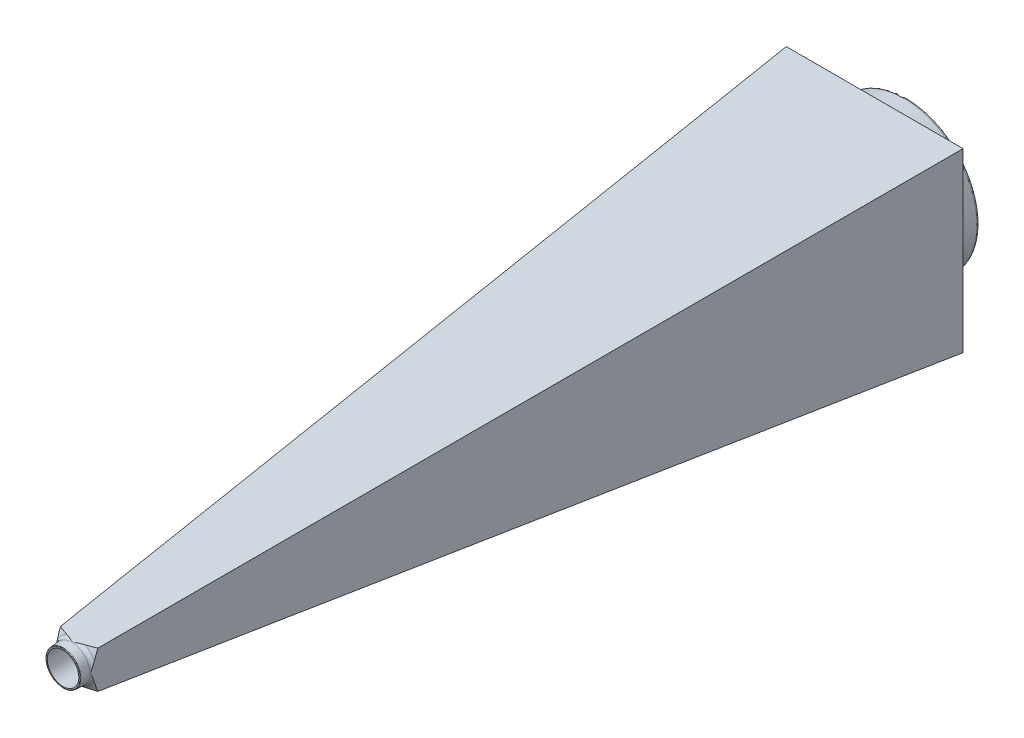
SolidWorks part; units mm, degrees
ref_plane "front" through (0, 0, 0) normal (0, 0, 1) x (1, 0, 0)
ref_plane "top" through (0, 0, 0) normal (0, 1, 0) x (1, 0, 0)
ref_plane "right" through (0, 0, 0) normal (1, 0, 0) x (0, 0, -1)
ref_axis "Axis1" through (0, 0, 50) along (0, 0, -1)
sketch "Sketch1" plane through (0, 0, 0) normal (1, 0, 0) x (0, 0, -1)
  line L0 (17.1291, 1.4986) -> (104.775, 9.1666)
  line L1 (17.1291, 3.0203) -> (104.775, 18.4747)
  line L2 (17.1291, 0) -> (104.775, 0) construction
  line L3 (104.775, 0) -> (104.775, 9.1666)
  line L4 (17.1291, 0) -> (17.1291, 1.4986)
  line L5 (17.1291, 2.3312) -> (34.9942, 4.7625)
  line L6 (72.2499, 9.1273) -> (89.0031, 11.2437)
  line L8 (104.775, 5.9795) -> (101.6, 5.7017)
  line L14 (103.9796, 4.0173) -> (43.9655, 1.397)
  line L15 (17.1291, 1.397) -> (43.9655, 1.397)
  point P0 (101.6, 8.8888)
  dimension "D2" = 10
  dimension "D3" = 17.7777
  dimension "D4" = 2.9972
  dimension "D5" = 3.175
  dimension "D6" = 6.0406
  dimension "D7" = 2.25
  dimension "D8" = 87.6459
  dimension "D9" = 17.1291
  dimension "D10" = 101.6
  dimension "D11" = 5
  dimension "D12" = 7.2
  dimension "D15" = 3.175
  dimension "D19" = 2.794
  dimension "D20" = 2.5
ref_plane "Plane1" through (0, 0, -17.1291) normal (0, 0, -1) x (-1, 0, 0)
ref_plane "Plane2" through (0, 0, -104.775) normal (0, 0, -1) x (-1, 0, 0)
sketch "Sketch2" plane through (0, 0, -17.1291) normal (0, 0, -1) x (-1, 0, 0)
  line L1 (1.4986, 1.4986) -> (-1.4986, 1.4986)
  line L2 (1.4986, 1.4986) -> (1.4986, -1.4986)
  line L3 (1.4986, -1.4986) -> (-1.4986, -1.4986)
  line L4 (-1.4986, 1.4986) -> (-1.4986, -1.4986)
  point P4 (-1.4986, 0)
sketch "Sketch3" plane through (0, 0, -104.775) normal (0, 0, -1) x (-1, 0, 0)
  line L1 (9.1666, 9.1666) -> (-9.1666, 9.1666)
  line L2 (9.1666, 9.1666) -> (9.1666, -9.1666)
  line L3 (9.1666, -9.1666) -> (-9.1666, -9.1666)
  line L4 (-9.1666, 9.1666) -> (-9.1666, -9.1666)
  point P4 (-9.1666, 0)
sketch3d "3DSketch1"
  line L0 (9.1666, 9.1666, -104.775) -> (1.4986, 1.4986, -17.1291)
sketch "Sketch17" plane through (0, 0, 0) normal (1, 0, 0) x (0, 0, -1)
  line L0 (105.41, 15.875) -> (105.41, 0)
  line L1 (105.41, 0) -> (17.1291, 0)
  line L2 (17.1291, 0) -> (17.1291, 2.1639)
  line L3 (72.2499, 9.1273) -> (89.0031, 11.2437) construction
  line L4 (105.41, 0) -> (124.5541, 0) construction
  line L6 (69.1652, 8.7376) -> (40.5902, 8.7376)
  line L7 (105.41, 15.875) -> (69.1652, 15.875)
  line L8 (69.1652, 15.875) -> (69.1652, 8.7376)
  line L9 (40.5902, 8.7376) -> (40.5902, 5.1277)
  line L10 (40.5902, 5.1277) -> (17.1291, 2.1639)
  dimension "D1" = 3.81
  dimension "D2" = 28.575
  dimension "D3" = 17.4752
  dimension "D4" = 31.75
revolve "BR-00 Lathe Initial" add sketch "Sketch17" angle 360 about L4
sketch "Sketch11" plane through (0, 0, 0) normal (1, 0, 0) x (0, 0, -1)
  line L5 (16.1202, 1.5875) -> (52.6835, 1.5875)
  line L6 (52.6835, 1.5875) -> (52.6835, 0)
  line L7 (17.1291, 0) -> (104.775, 0) construction
  line L8 (52.6835, 0) -> (16.1202, 0)
  line L9 (16.1202, 0) -> (16.1202, 1.5875)
  line L10 (16.1202, 0) -> (14.1068, 0) construction
  dimension "D2" = 3.175
revolve "CR-00 Bore at tip" cut sketch "Sketch11" angle 360 about axis through (0, 0, 50) along (0, 0, -1)
sketch "Sketch22" plane through (0, 0, 0) normal (0, 1, 0) x (1, 0, 0)
  line L0 (2.159, 14.5891) -> (5.1308, 14.5891)
  line L1 (5.1308, 14.5891) -> (5.1308, 38.1133)
  line L2 (5.1308, 38.1133) -> (2.159, 14.5891)
  line L3 (0, 0) -> (0, 16.6658)
  line L4 (-2.1639, 17.1291) -> (2.1639, 17.1291) construction
  line L5 (5.1308, 27.9803) -> (3.4391, 14.5891)
  line L6 (5.1308, 17.8473) -> (4.7192, 14.5891)
  line L7 (0, 17.1291) -> (7.3692, 17.1291)
  line L8 (6.3908, 37.9541) -> (3.419, 14.4299) construction
  line L9 (7.6508, 37.7949) -> (4.679, 14.2707) construction
  line L10 (-1.5875, 17.1291) -> (1.5875, 17.1291) construction
  dimension "D1" = 7.2
  dimension "D2" = 2.54
  dimension "D3" = 2.159
  dimension "D4" = 5.1308
  dimension "D5" = 1.27
  dimension "D6" = 1.27
sketch "Sketch16" plane through (0, 0, 0) normal (1, 0, 0) x (0, 0, -1)
  line L0 (15.5968, 0.762) -> (17.6371, 0.762)
  line L1 (17.6371, 0.762) -> (17.6371, 1.5367) construction
  line L2 (17.6371, 1.5367) -> (18.3305, 1.5974) construction
  line L3 (21.2443, 2.0697) -> (26.4988, 11.1707)
  line L4 (26.4988, 11.1707) -> (15.5968, 11.1707)
  line L5 (15.5968, 11.1707) -> (15.5968, 0.762)
  line L6 (17.1291, 0) -> (17.1291, 1.4986) construction
  line L7 (16.4674, 0) -> (13.7912, 0) construction
  line L8 (18.3305, 1.5974) -> (18.3305, 1.9038) construction
  line L9 (18.3305, 1.9038) -> (18.6531, 1.9038) construction
  line L10 (18.6531, 1.9038) -> (18.6531, 1.6256) construction
  line L11 (18.6531, 1.6256) -> (18.2177, 1.5875) construction
  line L12 (19.9597, 1.7399) -> (19.9597, 1.5875)
  line L13 (19.9597, 1.5875) -> (18.2177, 1.5875) construction
  line L14 (19.9597, 1.7399) -> (20.8487, 1.8177)
  line L15 (19.9597, 1.5875) -> (20.472, 1.5875)
  line L16 (20.472, 1.5875) -> (20.472, 0.762)
  line L17 (20.472, 0.762) -> (17.6371, 0.762)
  arc A0 (20.8487, 1.8177) -> (21.2443, 2.0697) centre (20.8044, 2.3237) ccw
  dimension "D5" = 0.508
  dimension "D1" = 0.508
  dimension "D2" = 1.524
  dimension "D3" = 3.0734
  dimension "D4" = 85
  dimension "D6" = 0.889
  dimension "D7" = 3.2512
  dimension "D8" = 60
  dimension "D9" = 95
  dimension "D10" = 0.1524
  dimension "D11" = 1.016
  dimension "D12" = 3.175
revolve "CR-00 Lathe at tip" cut sketch "Sketch16" angle 360 about L7
sketch "Sketch26" plane through (0, 0, 0) normal (1, 0, 0) x (0, 0, -1)
  line L0 (3.2879, 0) -> (53.4597, 0) construction
  line L1 (40.4575, -7.0345) -> (19.9597, -4.445)
  line L2 (19.9597, 0) -> (19.9597, -12.0071)
  line L3 (19.9597, -5.715) -> (40.4575, -8.3045)
  line L5 (40.4575, -5.7645) -> (19.9597, -3.175)
  line L6 (19.9597, 1.5875) -> (19.9597, -1.5875) construction
  dimension "D1" = 7.2
  dimension "D2" = 3.175
  dimension "D3" = 5.715
  dimension "D4" = 4.445
  dimension "D5" = 20.4978
sketch "Sketch7" plane through (0, 0, 0) normal (1, 0, 0) x (0, 0, -1)
  line L0 (42.9497, 0) -> (137.0382, 0)
  line L1 (137.0382, 0) -> (137.0382, 20.32)
  line L2 (17.1291, 1.4986) -> (104.775, 9.1666) construction
  line L3 (92.075, 6.35) -> (104.775, 6.35)
  line L8 (60.96, 3.9751) -> (57.785, 3.9751)
  line L9 (57.785, 3.9751) -> (42.9497, 0)
  line L10 (137.0382, 0) -> (151.0798, 0) construction
  line L11 (104.775, 6.35) -> (104.775, 7.366)
  line L12 (104.775, 7.366) -> (101.6, 7.366)
  line L13 (101.6, 7.366) -> (101.6, 20.32)
  line L14 (101.6, 20.32) -> (137.0382, 20.32)
  line L15 (60.96, 3.9751) -> (92.075, 6.35)
  point P3 (104.775, 3.0876)
  point P4 (62.5846, 0)
  dimension "D2" = 15
  dimension "D3" = 12.7
  dimension "D4" = 2.8059
  dimension "D5" = 7.9502
  dimension "D6" = 40.64
  dimension "D7" = 3.175
  dimension "D8" = 46.99
  dimension "D9" = 12.7
  dimension "D12" = 14.732
  dimension "D13" = 3.175
  dimension "D14" = 62.5846
revolve "CR-00 Bore form base ( flip around )" cut sketch "Sketch7" angle 360 about L10
sketch "Sketch20" plane through (0, 0, 0) normal (1, 0, 0) x (0, 0, -1)
  line L0 (105.41, 13.3164) -> (69.1652, 8.7376)
  line L1 (68.3077, 9.4936) -> (68.3077, 30.2892)
  line L2 (68.3077, 30.2892) -> (105.41, 30.2892)
  line L3 (105.41, 30.2892) -> (105.41, 13.3164)
  line L4 (113.5338, 0) -> (127.093, 0) construction
  line L5 (72.2499, 9.1273) -> (89.0031, 11.2437) construction
  line L6 (69.1652, 15.875) -> (69.1652, 8.7376) construction
  arc A0 (69.1652, 8.7376) -> (68.3077, 9.4936) centre (69.0697, 9.4936) cw
  dimension "D1" = 0.762
revolve "CR-00 Lathe Next" cut sketch "Sketch20" angle 360 about L4
sketch "Sketch28" plane through (0, 0, 0) normal (1, 0, 0) x (0, 0, -1)
  line L0 (107.6606, 0) -> (67.0871, 0) construction
  line L1 (68.9742, 0) -> (68.9742, 16.899)
  line L2 (68.9742, 8.7376) -> (68.9742, -8.7376) construction
  line L3 (68.9742, 9.5076) -> (95.25, 12.827)
  line L5 (88.265, 12.827) -> (68.9742, 10.39)
  line L6 (68.9742, 11.3526) -> (80.645, 12.827)
  line L9 (104.775, 12.827) -> (57.694, 12.827)
  line L11 (104.775, -6.35) -> (104.775, 6.35) construction
  dimension "D1" = 7.2
  dimension "D2" = 12.827
  dimension "D3" = 9.525
  dimension "D4" = 16.51
  dimension "D5" = 24.13
fillet "Fillet1" radius 0.254 1 edges at (7.366, 0, -104.775)
sketch "Sketch29" plane through (0, 0, 0) normal (1, 0, 0) x (0, 0, -1)
  line L0 (104.775, 0) -> (48.8744, 0) construction
  line L1 (104.775, -6.35) -> (104.775, 6.35) construction
  line L2 (48.8744, 1.5875) -> (48.8744, -1.5875) construction
  line L3 (60.96, 3.5712) -> (92.075, 3.5712)
  line L4 (60.96, 3.9751) -> (60.96, -3.9751) construction
  line L5 (92.075, 6.35) -> (92.075, -6.35) construction
  line L6 (60.96, 3.7182) -> (92.075, 6.096)
  line L7 (67.3703, 3.5712) -> (92.075, 5.4591)
  line L8 (75.704, 3.5712) -> (92.075, 4.8223)
  line L9 (84.0377, 3.5712) -> (92.075, 4.1854)
  line L10 (63.3555, 3.9013) -> (92.0745, 6.096) construction
  line L11 (63.5007, 2.0018) -> (92.2197, 4.1965) construction
  line L12 (63.4039, 3.2681) -> (92.1229, 5.4628) construction
  line L16 (63.4523, 2.635) -> (92.1713, 4.8297) construction
  line L17 (104.775, 0) -> (104.775, 15.2377)
  dimension "D1" = 3.5712
  dimension "D5" = 4.37
  dimension "D6" = 6.096
  dimension "D2" = 0.635
  dimension "D3" = 0.635
  dimension "D4" = 0.635
sketch "Sketch18" plane through (0, 0, 0) normal (1, 0, 0) x (0, 0, -1)
  line L0 (125.7782, 11.0042) -> (12.7336, 1.114)
  line L1 (12.7336, 1.114) -> (12.7336, 41.9525)
  line L2 (12.7336, 41.9525) -> (125.7782, 41.9525)
  line L3 (125.7782, 41.9525) -> (125.7782, 11.0042)
extrude "CE-00 Mill one side flat" cut sketch "Sketch18" against normal mid plane 25.4
pattern_circular "CP-00 Mill pattern" count 4 over 360 about axis through (0, 0, 0) along (0, 0, 1) of "CE-00 Mill one side flat"
sketch "Sketch23" plane through (0, 0, 0) normal (1, 0, 0) x (0, 0, -1)
  line L0 (116.84, 6.35) -> (116.84, 4.826)
  line L1 (116.84, 4.826) -> (116.078, 4.826)
  line L2 (116.078, 4.826) -> (116.078, 0)
  line L3 (116.078, 0) -> (223.7832, 0)
  line L4 (223.7832, 0) -> (223.7832, 15.6972)
  line L5 (223.7832, 15.6972) -> (207.8817, 15.6972)
  line L6 (207.8817, 15.6972) -> (207.8817, 13.6652)
  line L7 (207.8817, 13.6652) -> (207.0192, 13.6652)
  line L8 (207.0192, 13.6652) -> (207.0192, 15.8623)
  line L9 (207.0192, 15.8623) -> (156.2192, 15.8623)
  line L10 (156.2192, 15.8623) -> (139.7, 18.7751)
  line L11 (139.7, 18.7751) -> (137.789, 7.9375)
  line L12 (137.789, 7.9375) -> (134.62, 7.9375)
  line L13 (134.62, 7.9375) -> (134.62, 6.35)
  line L14 (134.62, 6.35) -> (116.84, 6.35)
  line L15 (223.7832, 0) -> (239.4804, 0) construction
  dimension "D1" = 10
  dimension "D2" = 1.524
  dimension "D3" = 12.7
  dimension "D4" = 16.764
  dimension "D5" = 0.8625
  dimension "D6" = 84.0832
  dimension "D7" = 2.9128
  dimension "D8" = 139.7
  dimension "D9" = 22.86
  dimension "D10" = 17.78
  dimension "D11" = 31.7246
  dimension "D12" = 31.3944
  dimension "D13" = 2.032
  dimension "D14" = 0.762
  dimension "D15" = 15.875
  dimension "D16" = 37.5502
  dimension "D18" = 16.5192
  dimension "D19" = 50.8
revolve "RB-00 Tool collet Body ( config )" [suppressed] add sketch "Sketch23" angle 360 about L15
sketch "Sketch25" plane through (0, 0, 0) normal (1, 0, 0) x (0, 0, -1)
  line L0 (134.62, 6.35) -> (116.84, 6.35) construction
  line L1 (114.3, 8.89) -> (133.604, 8.89)
  line L2 (114.3, 8.89) -> (114.3, 3.175)
  line L3 (114.3, 3.175) -> (133.604, 3.175)
  line L4 (133.604, 8.89) -> (133.604, 3.175)
  line L5 (134.62, 7.9375) -> (134.62, 6.35) construction
  line L6 (116.84, 6.35) -> (116.84, 4.826) construction
  dimension "D1" = 3.175
  dimension "D2" = 1.016
  dimension "D3" = 2.54
  dimension "D4" = 2.54
extrude "CE-00 Tool collet slot one" [suppressed] cut sketch "Sketch25" against normal mid plane 1.016
pattern_circular "CP-00 Tool collet slot more" [suppressed] count 4 over 360 about axis through (0, 0, 50) along (0, 0, -1)
sketch "Sketch24" plane through (0, 0, 0) normal (1, 0, 0) x (0, 0, -1)
  line L0 (15.875, 0) -> (-76.5302, 0)
  line L2 (-63.8302, 7.6009) -> (4.7498, 9.0297)
  line L3 (4.7498, 9.0297) -> (6.35, 8.1058)
  line L4 (6.35, 8.1058) -> (6.35, 1.5875)
  line L5 (6.35, 1.5875) -> (15.875, 1.5875)
  line L6 (15.875, 1.5875) -> (15.875, 0)
  line L7 (-76.5302, 0) -> (-82.0991, 0) construction
  line L8 (6.35, 8.1058) -> (20.3897, 0) construction
  line L9 (-63.8302, 7.6009) -> (-64.8462, 6.5849)
  line L10 (-64.8462, 6.5849) -> (-75.5142, 6.5849)
  line L11 (-75.5142, 6.5849) -> (-76.5302, 5.5689)
  line L12 (-76.5302, 5.5689) -> (-76.5302, 0)
  dimension "D1" = 15.2019
  dimension "D2" = 1.193
  dimension "D3" = 30
  dimension "D4" = 3.175
  dimension "D5" = 9.525
  dimension "D6" = 68.58
  dimension "D7" = 15.875
  dimension "D8" = 1.6002
  dimension "D9" = 18.0594
  dimension "D10" = 45
  dimension "D12" = 1.016
  dimension "D13" = 1.016
  dimension "D14" = 12.7
revolve "RB-00 Tool center for tip" [suppressed] add sketch "Sketch24" angle 360 about L7
sketch "Sketch27" plane through (0, 0, -101.6) normal (0, 0, -1) x (-1, 0, 0)
  circle A0 centre (0, 0) radius 12.7
  dimension "D1" = 25.4
fillet "Fillet2" radius 0.0508 1 edges at (-1.7399, 0, -19.9597)
sketch "Sketch30" plane through (0, 0, 0) normal (-0.9962, 0, 0.0872) x (0.0872, 0, 0.9962)
  line L0 (-101.9881, 8.8888) -> (-21.6742, 1.889) construction
  line L1 (-101.9881, 8.8888) -> (-101.9881, -8.8888) construction
  line L2 (-101.9881, 8.8888) -> (-21.6742, 1.889)
  line L3 (-101.9881, 8.8888) -> (-101.9881, -8.8888)
  line L4 (-21.6742, 1.889) -> (-21.6742, -7.636)
  dimension "D1" = 9.525
sketch "Sketch31" plane through (0, 0, 0) normal (-0.9962, 0, 0.0872) x (0.0872, 0, 0.9962)
  line L1 (-101.9881, 8.8888) -> (-101.9881, -8.8888) construction
  line L2 (-101.9881, 8.8888) -> (-21.6742, 1.889) construction
  line L3 (-101.9881, 18.45) -> (-101.9881, -8.8888)
  line L4 (-101.9881, 8.8888) -> (-21.6742, 1.889) construction
  line L5 (-101.9881, 18.45) -> (-29.2389, 12.1094)
  line L6 (-101.9881, 18.45) -> (-101.9881, -8.8888) construction
  line L7 (-101.9881, 18.45) -> (-29.2389, 12.1094) construction
  dimension "D2" = 73.025
  dimension "D1" = 9.525
sketch "Sketch32" plane through (0, 0, 0) normal (0, 0.9962, 0.0872) x (1, 0, 0)
  line L0 (0, 21.2883) -> (0, 19.3942)
